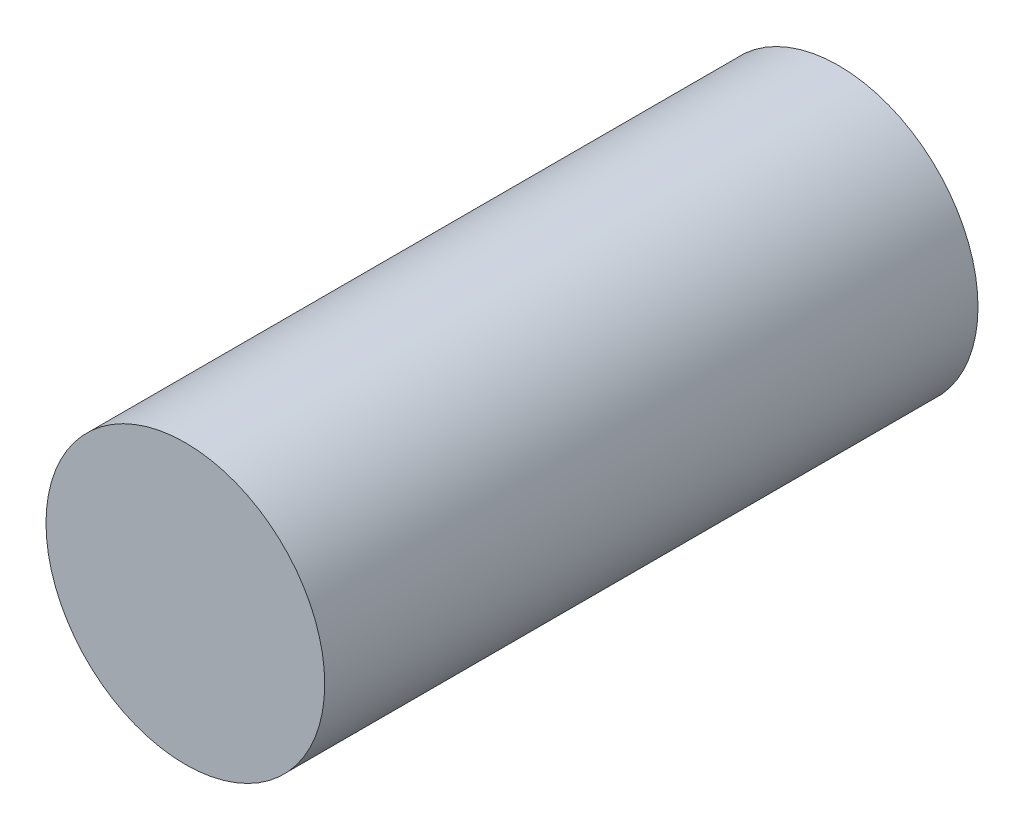
SolidWorks part; units mm, degrees
ref_plane "Front Plane" through (0, 0, 0) normal (0, 0, 1) x (1, 0, 0)
ref_plane "Top Plane" through (0, 0, 0) normal (0, 1, 0) x (1, 0, 0)
ref_plane "Right Plane" through (0, 0, 0) normal (1, 0, 0) x (0, 0, -1)
sketch "Sketch2" plane through (0, 0, 0) normal (0, 0, 1) x (1, 0, 0)
  circle A0 centre (0, 0) radius 64
  dimension "D1" = 128
extrude "Boss-Extrude1" add sketch "Sketch2" along normal blind 300 contours A0
sketch "Sketch3" plane through (0, 0, 0) normal (0, 0, 1) x (1, 0, 0)
  circle A0 centre (0, 0) radius 60
  dimension "D1" = 120
extrude "Cut-Extrude1" cut sketch "Sketch3" along normal blind 280 from offset 10
